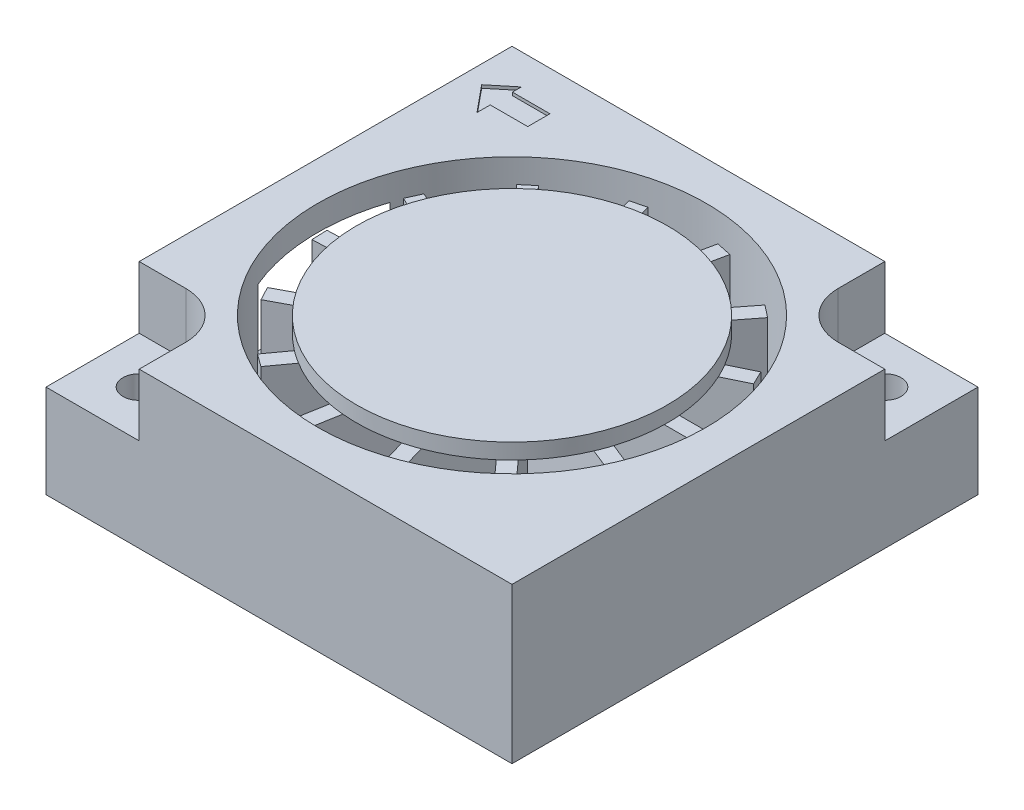
SolidWorks part; units mm, degrees
ref_plane "前视基准面" through (0, 0, 0) normal (0, 0, 1) x (1, 0, 0)
ref_plane "上视基准面" through (0, 0, 0) normal (0, 1, 0) x (1, 0, 0)
ref_plane "右视基准面" through (0, 0, 0) normal (1, 0, 0) x (0, 0, -1)
sketch "草图1" plane through (0, 0, 0) normal (0, 1, 0) x (1, 0, 0)
  line L1 (0, 0) -> (30, 0)
  line L2 (0, 0) -> (0, -30)
  line L3 (0, -30) -> (30, -30)
  line L4 (30, 0) -> (30, -30)
  dimension "D1" = 30
  dimension "D2" = 30
extrude "凸台-拉伸1" add sketch "草图1" along normal blind 10
sketch "草图2" plane through (0, 10, 0) normal (0, 1, 0) x (1, 0, 0)
  line L1 (0, -30) -> (6, -30)
  line L2 (0, -30) -> (0, -24)
  line L3 (0, -24) -> (6, -24)
  line L4 (6, -30) -> (6, -24)
  line L5 (30, 0) -> (24, 0)
  line L6 (30, 0) -> (30, -6)
  line L7 (30, -6) -> (24, -6)
  line L8 (24, 0) -> (24, -6)
  dimension "D1" = 6
  dimension "D2" = 6
  dimension "D3" = 6
  dimension "D4" = 6
extrude "切除-拉伸1" cut sketch "草图2" against normal blind 4
sketch "草图3" plane through (0, 10, 0) normal (0, 1, 0) x (1, 0, 0)
  line L0 (15, -15) -> (30, -15) construction
  line L1 (30, -30) -> (30, -6) construction
  line L2 (15, -15) -> (15, -30) construction
  line L3 (6, -30) -> (30, -30) construction
  line L4 (15, -15) -> (0, -15) construction
  line L5 (0, 0) -> (0, -24) construction
  line L6 (15, -15) -> (15, 0) construction
  line L7 (24, 0) -> (0, 0) construction
  circle A0 centre (15, -15) radius 12.5
  dimension "D1" = 25
extrude "切除-拉伸2" cut sketch "草图3" against normal blind 8
fillet "圆角1" radius 3 1 edges at (6, 8, 24)
fillet "圆角2" radius 3 1 edges at (24, 8, 6)
sketch "草图4" plane through (0, 10, 0) normal (0, 1, 0) x (1, 0, 0)
  line L0 (2.5682, -1.965) -> (1.1656, -3.1182)
  line L1 (1.1656, -3.1182) -> (2.5682, -4.8241)
  line L2 (2.5682, -4.8241) -> (2.5682, -3.9711)
  line L3 (2.5682, -3.9711) -> (4.9838, -3.9711)
  line L4 (4.9838, -3.9711) -> (4.9838, -2.5416)
  line L5 (4.9838, -2.5416) -> (2.5682, -2.5416)
  line L6 (2.5682, -2.5416) -> (2.5682, -1.965)
extrude "切除-拉伸3" cut sketch "草图4" against normal blind 0.2
sketch "草图5" plane through (0, 6, 0) normal (0, 1, 0) x (1, 0, 0)
  line L0 (3, -27) -> (3, -30) construction
  line L1 (0, -30) -> (6, -30) construction
  line L2 (3, -27.4233) -> (0, -27.4233) construction
  line L3 (0, -24) -> (0, -30) construction
  line L4 (27, -3) -> (30, -3) construction
  line L5 (30, -6) -> (30, 0) construction
  line L6 (27, -3) -> (27, 0) construction
  line L7 (30, 0) -> (24, 0) construction
  circle A0 centre (3, -27) radius 1.05
  circle A1 centre (27, -3) radius 1.05
  dimension "D1" = 2.1
  dimension "D2" = 3
extrude "切除-拉伸4" cut sketch "草图5" against normal blind 10
sketch "草图6" plane through (0, 2, 0) normal (0, 1, 0) x (1, 0, 0)
  line L1 (15, -14.1932) -> (26.6998, -14.1932)
  line L2 (15, -14.1932) -> (15, -15.1932)
  line L3 (15, -15.1932) -> (26.6998, -15.1932)
  line L4 (26.6998, -14.1932) -> (26.6998, -15.1932)
  circle A0 centre (15, -15) radius 8.4567 construction
  circle A1 centre (15, -15) radius 12.5 construction
  dimension "D1" = 0
  dimension "D2" = 1
extrude "凸台-拉伸2" add sketch "草图6" along normal blind 7
pattern_circular "阵列(圆周)1" count 14 every 26 about axis through (15, 0, 15) along (0, 1, 0) of "凸台-拉伸2"
sketch "草图7" plane through (0, 9, 0) normal (0, 1, 0) x (1, 0, 0)
  circle A0 centre (15, -15) radius 10
  circle A1 centre (15, -15) radius 12.5 construction
  dimension "D1" = 0
  dimension "D2" = 20
sketch "草图8" plane through (0, 0, 0) normal (-1, 0, 0) x (0, 0, 1)
  line L1 (1.44, 8.3746) -> (22.5196, 8.3746)
  line L2 (1.44, 8.3746) -> (1.44, 1.194)
  line L3 (1.44, 1.194) -> (22.5196, 1.194)
  line L4 (22.5196, 8.3746) -> (22.5196, 1.194)
extrude "切除-拉伸6" cut sketch "草图8" against normal up to surface (3.5557 mm away)
extrude "凸台-拉伸3" add sketch "草图7" along normal up to surface (1 mm away) up to face at (3.058, 10, 3.2761)
